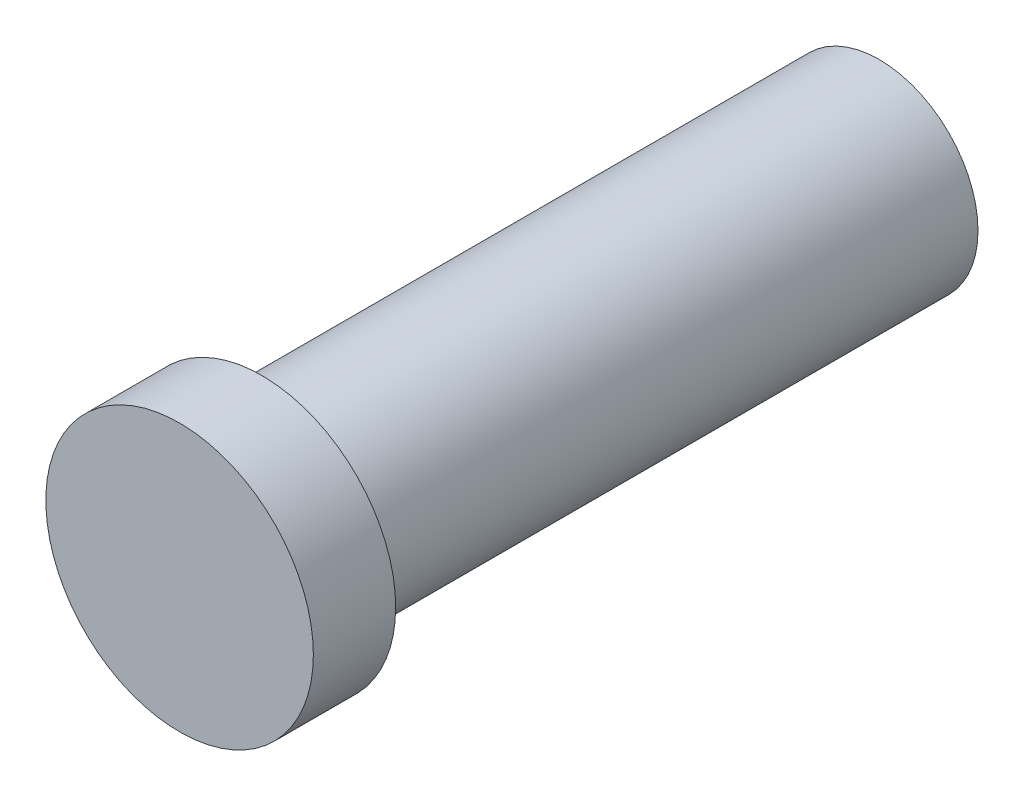
SolidWorks part; units mm, degrees
ref_plane "Front Plane" through (0, 0, 0) normal (0, 0, 1) x (1, 0, 0)
ref_plane "Top Plane" through (0, 0, 0) normal (0, 1, 0) x (1, 0, 0)
ref_plane "Right Plane" through (0, 0, 0) normal (1, 0, 0) x (0, 0, -1)
sketch "Sketch1" plane through (0, 0, 0) normal (0, 0, 1) x (1, 0, 0)
  circle A0 centre (0, 0) radius 4.8
  dimension "D1" = 9.6
extrude "Boss-Extrude1" add sketch "Sketch1" along normal blind 30
sketch "Sketch2" plane through (0, 0, 30) normal (0, 0, 1) x (1, 0, 0)
  circle A0 centre (0, 0) radius 6.5
  dimension "D1" = 13
extrude "Boss-Extrude2" add sketch "Sketch2" along normal blind 4
sketch "Sketch3" plane through (0, 0, 0) normal (0, 0, -1) x (-1, 0, 0)
  circle A0 centre (0, 0) radius 3.5
  dimension "D1" = 7
extrude "Cut-Extrude1" cut sketch "Sketch3" against normal blind 15 draft 6
